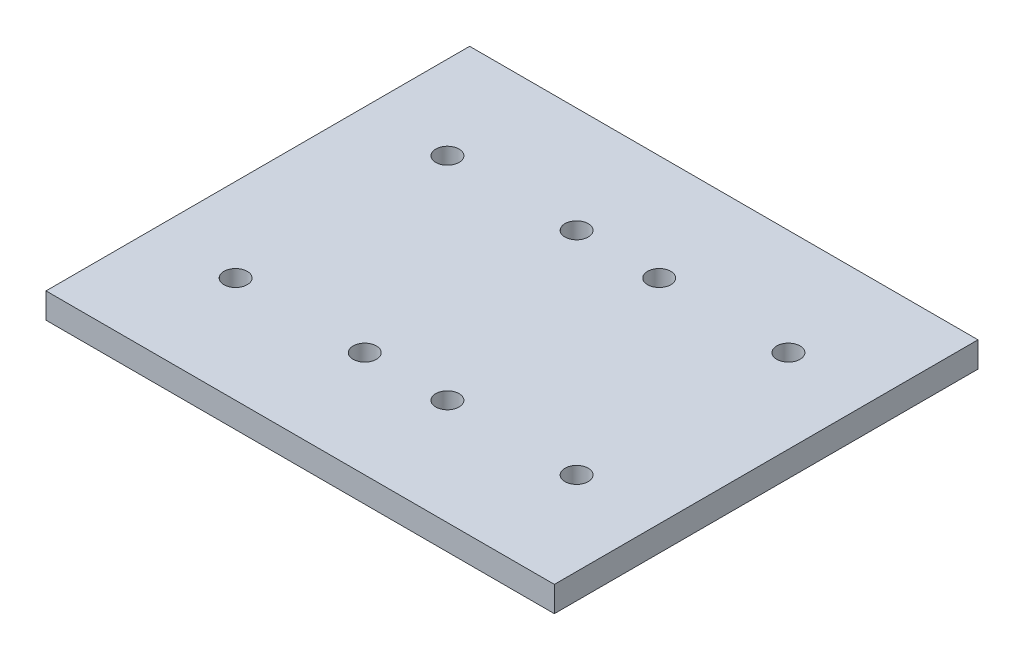
SolidWorks part; units mm, degrees
ref_plane "Plano frontal" through (0, 0, 0) normal (0, 0, 1) x (1, 0, 0)
ref_plane "Plano superior" through (0, 0, 0) normal (0, 1, 0) x (1, 0, 0)
ref_plane "Plano direito" through (0, 0, 0) normal (1, 0, 0) x (0, 0, -1)
sketch "Esboço1" plane through (0, 0, 0) normal (0, 1, 0) x (1, 0, 0)
  line L1 (-60, 50) -> (60, 50)
  line L2 (-60, 50) -> (-60, -50)
  line L3 (-60, -50) -> (60, -50)
  line L4 (60, 50) -> (60, -50)
  line L5 (-60, 50) -> (60, -50) construction
  line L6 (-60, -50) -> (60, 50) construction
  point P0 (0, 0)
  dimension "D1" = 120
  dimension "D2" = 100
extrude "Ressalto-extrusão1" add sketch "Esboço1" along normal blind 6
sketch "Esboço2" plane through (0, 6, 0) normal (0, 1, 0) x (1, 0, 0)
  line L0 (0, 50) -> (0, -50) construction
  line L1 (9.75, 25) -> (40.25, 25) construction
  line L2 (60, 50) -> (-60, 50) construction
  line L3 (-60, -50) -> (60, -50) construction
  circle A0 centre (9.75, 25) radius 2.75
  circle A1 centre (40.25, 25) radius 2.75
  circle A2 centre (9.75, -25) radius 2.75
  circle A7 centre (40.25, -25) radius 2.75
  circle A8 centre (-40.25, -25) radius 2.75
  circle A9 centre (-9.75, -25) radius 2.75
  circle A10 centre (-40.25, 25) radius 2.75
  circle A11 centre (-9.75, 25) radius 2.75
  point P6 (0, 50)
  point P7 (25, 25)
  point P10 (0, -50)
  dimension "D1" = 5.5
  dimension "D2" = 50
  dimension "D3" = 30.5
  dimension "D4" = 25
  dimension "D5" = 25
extrude "Corte-extrusão1" cut sketch "Esboço2" against normal through all
